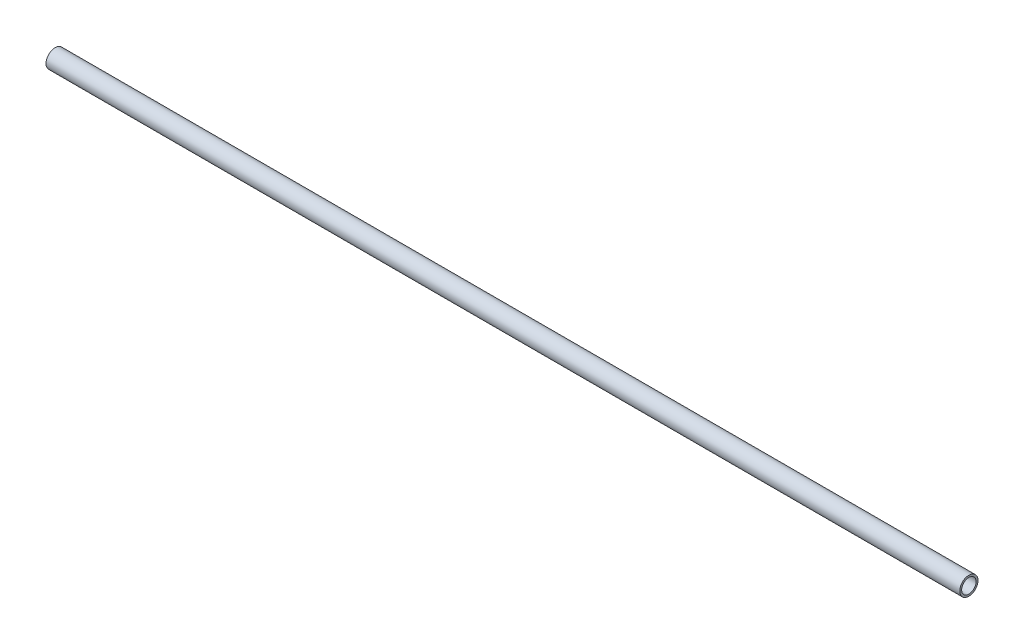
SolidWorks part; units mm, degrees
ref_plane "Alzado" through (0, 0, 0) normal (0, 0, 1) x (1, 0, 0)
ref_plane "Planta" through (0, 0, 0) normal (0, 1, 0) x (1, 0, 0)
ref_plane "Vista lateral" through (0, 0, 0) normal (1, 0, 0) x (0, 0, -1)
sketch "Croquis1" plane through (0, 0, 0) normal (1, 0, 0) x (0, 0, -1)
  circle A0 centre (0, 0) radius 19
  circle A1 centre (0, 0) radius 15
extrude "Saliente-Extruir1" add sketch "Croquis1" along normal blind 1900
